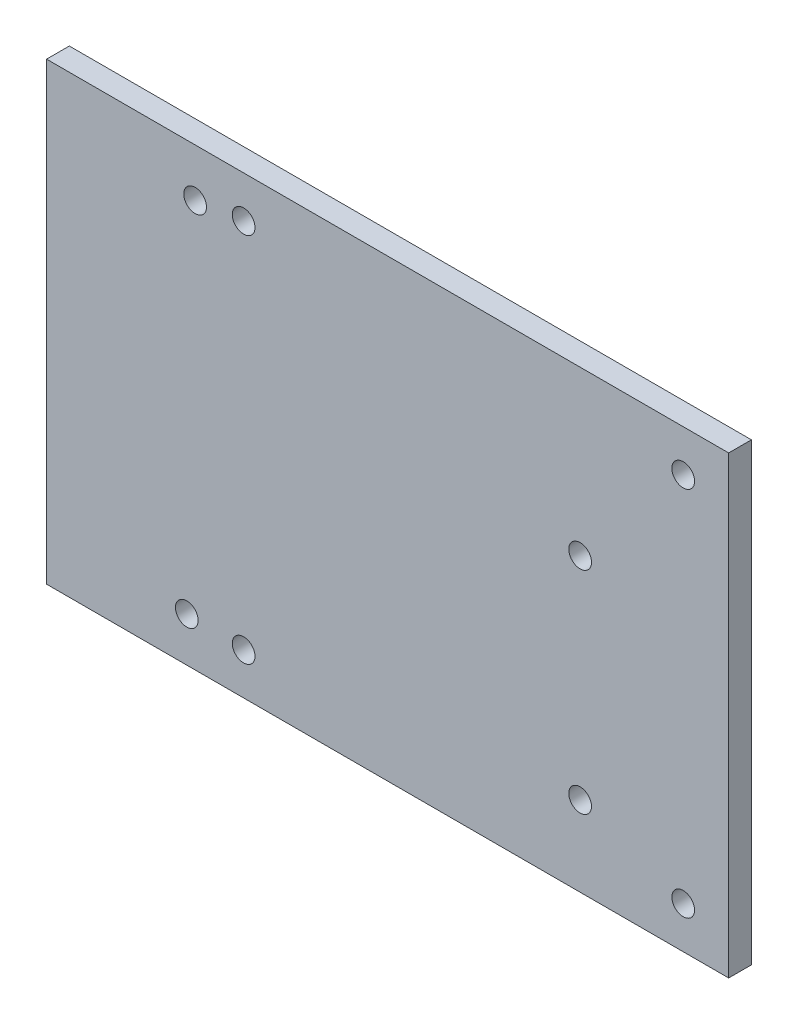
SolidWorks part; units mm, degrees
material "ABS"
ref_plane "Front Plane" through (0, 0, 0) normal (0, 0, 1) x (1, 0, 0)
ref_plane "Top Plane" through (0, 0, 0) normal (0, 1, 0) x (1, 0, 0)
ref_plane "Right Plane" through (0, 0, 0) normal (1, 0, 0) x (0, 0, -1)
sketch "Sketch1" plane through (0, 0, 0) normal (0, 0, 1) x (1, 0, 0)
  line L4 (-45, -30) -> (-45, 30)
  line L9 (-45, 30) -> (45, 30)
  line L10 (45, 30) -> (45, -30)
  line L11 (45, -30) -> (-45, -30)
  circle A0 centre (-25.4, 23.65) radius 1.5
  circle A1 centre (-26.5, -24.15) radius 1.5
  circle A2 centre (25.4, -19.45) radius 1.5
  circle A3 centre (25.4, 8.45) radius 1.5
  circle A4 centre (-19, -24.5) radius 1.5
  circle A5 centre (-19, 24.5) radius 1.5
  circle A6 centre (39, 24.5) radius 1.5
  circle A7 centre (39, -24.5) radius 1.5
  point P0 (0, 0)
  point P14 (63.6305, 26.65)
  dimension "D2" = 3
  dimension "D1" = 1.1
  dimension "D4" = 50.8
  dimension "D7" = 51.9
  dimension "D11" = 90
  dimension "D12" = 60
  dimension "D13" = 58
  dimension "D14" = 49
  dimension "D15" = 58
  dimension "D16" = 49
  dimension "D17" = 5.5
  dimension "D18" = 5.5
  dimension "D19" = 26
extrude "Boss-Extrude1" add sketch "Sketch1" along normal blind 3
